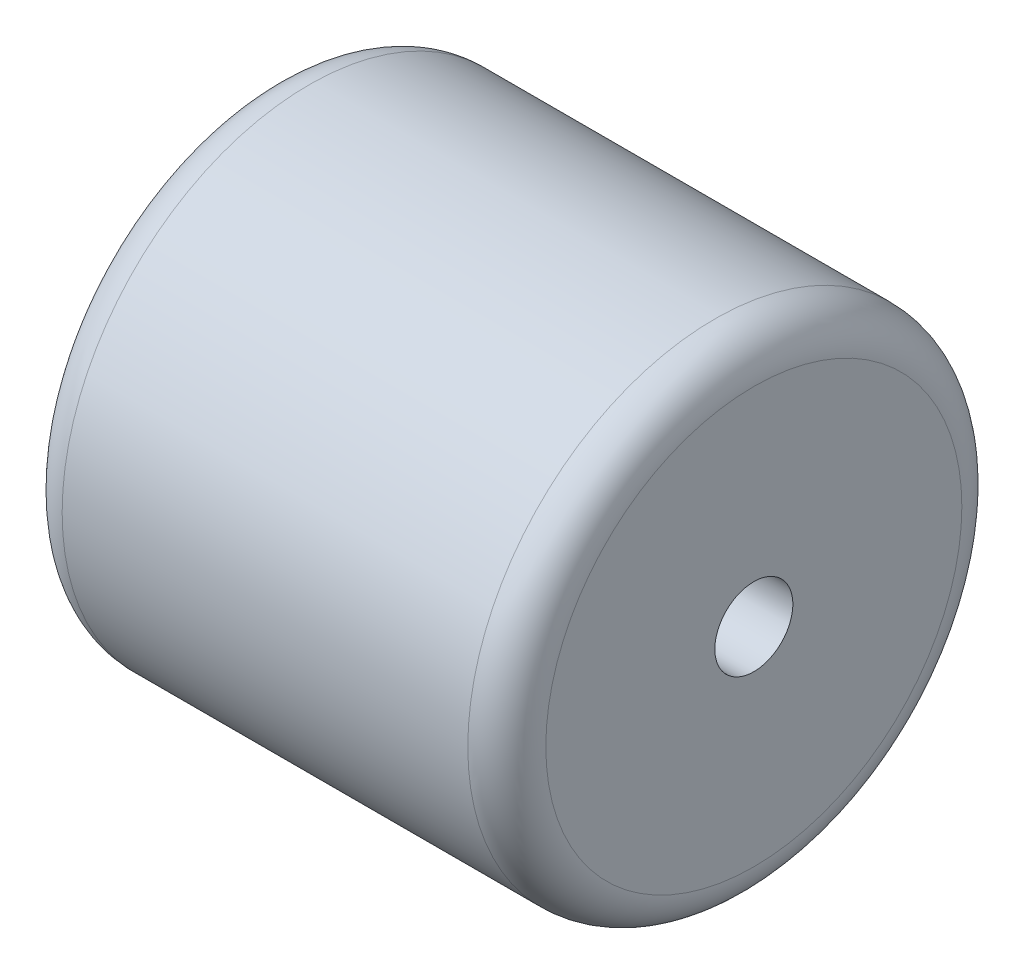
SolidWorks part; units mm, degrees
ref_plane "Front Plane" through (0, 0, 0) normal (0, 0, 1) x (1, 0, 0)
ref_plane "Top Plane" through (0, 0, 0) normal (0, 1, 0) x (1, 0, 0)
ref_plane "Right Plane" through (0, 0, 0) normal (1, 0, 0) x (0, 0, -1)
sketch "Sketch1" plane through (0, 0, 0) normal (0, 0, 1) x (1, 0, 0)
  line L0 (-3.8728, 0) -> (5.0903, 0) construction
  line L1 (-9.3, 1.5) -> (9.3, 1.5)
  line L2 (-9.3, 1.5) -> (-9.3, 8)
  line L3 (-7.8, 9.5) -> (7.8, 9.5)
  line L4 (9.3, 1.5) -> (9.3, 8)
  arc A0 (7.8, 9.5) -> (9.3, 8) centre (7.8, 8) cw
  arc A1 (-9.3, 8) -> (-7.8, 9.5) centre (-7.8, 8) cw
  point P4 (0, 1.5)
  point P8 (9.3, 9.5)
  point P11 (-9.3, 9.5)
  dimension "D3" = 1.5
  dimension "D1" = 8
  dimension "D2" = 18.6
  dimension "D4" = 1.5
revolve "Revolve1" add sketch "Sketch1" angle 360 about L0
